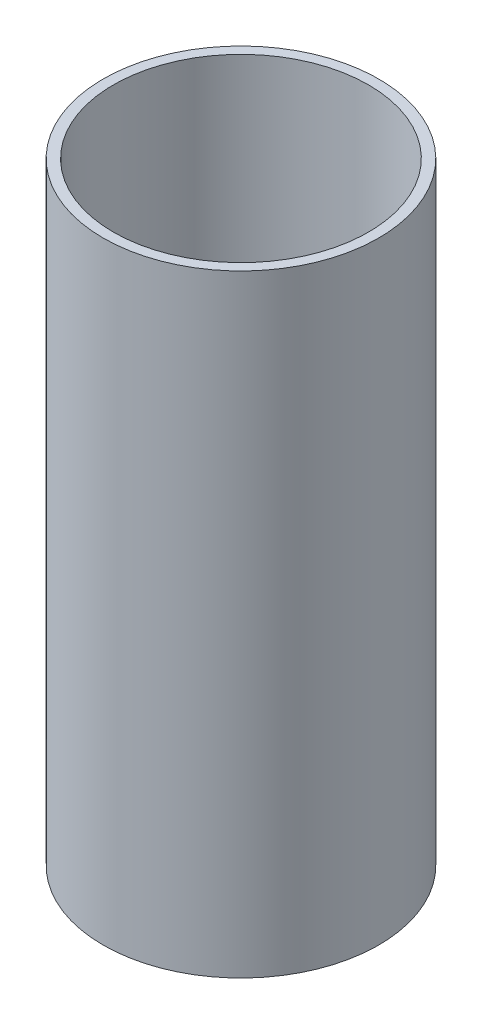
SolidWorks part; units mm, degrees
material "Hexcel AS4C (3000 Filamentos)"
ref_plane "Plano frontal" through (0, 0, 0) normal (0, 0, 1) x (1, 0, 0)
ref_plane "Plano superior" through (0, 0, 0) normal (0, 1, 0) x (1, 0, 0)
ref_plane "Plano direito" through (0, 0, 0) normal (1, 0, 0) x (0, 0, -1)
sketch "Esboço1" plane through (0, 0, 0) normal (0, 1, 0) x (1, 0, 0)
  circle A0 centre (0, 0) radius 27
  circle A1 centre (0, 0) radius 25
extrude "Ressalto-extrusão1" add sketch "Esboço1" along normal blind 120
